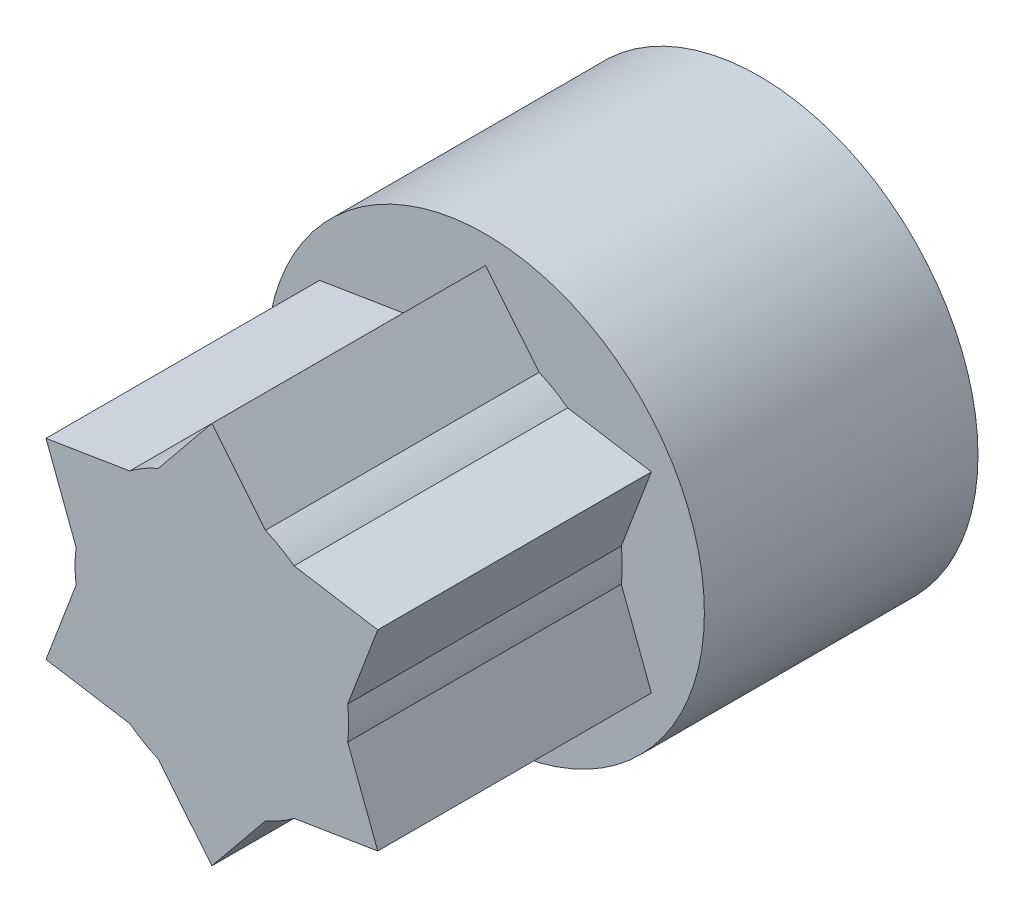
SolidWorks part; units mm, degrees
ref_plane "Спереди" through (0, 0, 0) normal (0, 0, 1) x (1, 0, 0)
ref_plane "Сверху" through (0, 0, 0) normal (0, 1, 0) x (1, 0, 0)
ref_plane "Справа" through (0, 0, 0) normal (1, 0, 0) x (0, 0, -1)
ref_plane "Плоскость1" through (0, 0, 31.603) normal (0, 0, 1) x (1, 0, 0)
sketch "Эскиз2" plane through (0, 0, 31.603) normal (0, 0, 1) x (1, 0, 0)
  line L2 (-0.9798, 2.3) -> (0, 3.5)
  line L3 (2.4818, 0.3015) -> (3.0311, 1.75)
  line L4 (0.9798, 2.3) -> (0, 3.5)
  line L5 (1.502, 1.9985) -> (3.0311, 1.75)
  line L6 (1.502, -1.9985) -> (3.0311, -1.75)
  line L7 (2.4818, -0.3015) -> (3.0311, -1.75)
  line L8 (-0.9798, -2.3) -> (0, -3.5)
  line L9 (0.9798, -2.3) -> (0, -3.5)
  line L10 (-2.4818, -0.3015) -> (-3.0311, -1.75)
  line L11 (-1.502, -1.9985) -> (-3.0311, -1.75)
  line L12 (-1.502, 1.9985) -> (-3.0311, 1.75)
  line L13 (-2.4818, 0.3015) -> (-3.0311, 1.75)
  circle A0 centre (0, 0) radius 4
  circle A1 centre (0, 0) radius 2.5
  point P24 (0, 0)
  dimension "D1" = 6
extrude "Бобышка-Вытянуть2" add sketch "Эскиз2" along normal blind 5 contours A1 L4 L2 | A1 L3 L5 | A1 L6 L7 | A1 L8 L9 | A1 L12 L13 | A1 L10 L11 | A1
sketch "Эскиз3" plane through (0, 0, 31.603) normal (0, 0, 1) x (1, 0, 0)
  circle A0 centre (0, 0) radius 4
extrude "Бобышка-Вытянуть4" add sketch "Эскиз3" against normal blind 5
